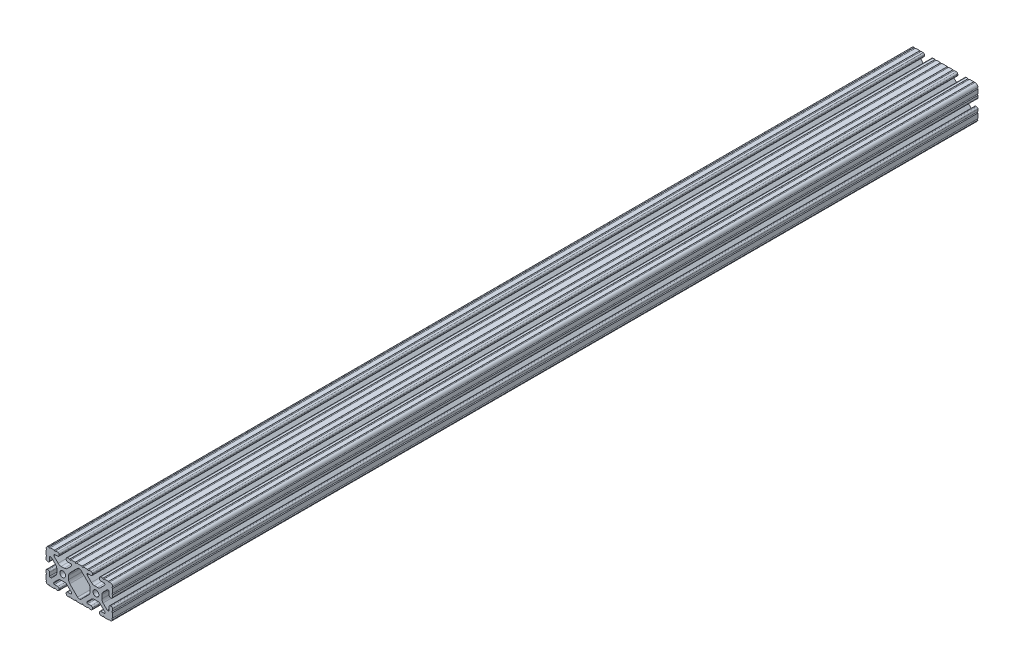
SolidWorks part; units mm, degrees
material "6061 Alloy"
ref_plane "Front Plane" through (0, 0, 0) normal (0, 0, 1) x (1, 0, 0)
ref_plane "Top Plane" through (0, 0, 0) normal (0, 1, 0) x (1, 0, 0)
ref_plane "Right Plane" through (0, 0, 0) normal (1, 0, 0) x (0, 0, -1)
sketch "Sketch1" plane through (0, 0, 0) normal (0, 0, 1) x (1, 0, 0)
  line L0 (-3.1211, -19.05) -> (3.1211, -19.05)
  line L1 (-38.1, 10.287) -> (-38.1, 14.3752)
  line L2 (0, -34.5561) -> (0, 32.8014) construction
  line L3 (-38.1, 0) -> (0, 0) construction
  line L4 (-38.1, 9.5497) -> (-38.1, 10.287)
  line L5 (-19.05, 19.05) -> (-19.05, -20.2827) construction
  line L6 (0, -15.1247) -> (0, -15.1131) construction
  line L7 (9.1761, 12.9058) -> (13.8525, 8.2294)
  line L8 (8.9158, 14.097) -> (8.9158, 13.5344)
  line L9 (13.4112, 14.986) -> (9.8048, 14.986)
  line L10 (14.986, 17.4968) -> (14.986, 16.5608)
  line L11 (10.9975, 19.05) -> (13.4328, 19.05)
  line L12 (8.6331, 19.05) -> (9.4735, 19.05)
  line L13 (4.6451, 19.05) -> (8.6331, 19.05)
  line L14 (31.792, 10.0266) -> (27.1976, 5.4321)
  line L15 (33.147, 10.287) -> (32.4207, 10.287)
  line L16 (29.2071, 19.05) -> (33.2963, 19.05)
  line L17 (28.4698, 19.05) -> (29.2071, 19.05)
  line L18 (-38.1, 5.6388) -> (-38.1, 8.0257)
  line L19 (24.5589, 19.05) -> (26.9458, 19.05)
  line L20 (23.114, 16.5608) -> (23.114, 17.4806)
  line L21 (28.2952, 14.986) -> (24.6888, 14.986)
  line L22 (29.1842, 13.5344) -> (29.1842, 14.097)
  line L23 (-34.036, 9.398) -> (-34.036, 5.6388)
  line L24 (-35.6108, 4.064) -> (-36.5252, 4.064)
  line L25 (24.2475, 8.2294) -> (28.9239, 12.9058)
  line L26 (25.8064, -2.0735) -> (25.8064, 2.0735)
  line L27 (35.6108, 4.064) -> (36.5252, 4.064)
  line L28 (34.036, 9.398) -> (34.036, 5.6388)
  line L29 (38.1, 5.6388) -> (38.1, 8.0257)
  line L30 (38.1, 9.5497) -> (38.1, 10.287)
  line L31 (38.1, 10.287) -> (38.1, 14.3752)
  line L32 (17.2111, 6.8382) -> (20.8889, 6.8382)
  line L33 (2.077, 14.2576) -> (10.9024, 5.4321)
  line L34 (-31.792, -10.0266) -> (-27.1976, -5.4321)
  line L35 (-33.147, -10.287) -> (-32.4207, -10.287)
  line L36 (-29.2071, -19.05) -> (-34.0473, -19.05)
  line L37 (-28.4698, -19.05) -> (-29.2071, -19.05)
  line L38 (-24.6888, -19.05) -> (-26.9458, -19.05)
  line L39 (12.2936, -2.0735) -> (12.2936, 2.0735)
  line L40 (-23.114, -16.5608) -> (-23.114, -17.4752)
  line L41 (-28.448, -14.986) -> (-24.6888, -14.986)
  line L42 (-29.337, -13.6872) -> (-29.337, -14.097)
  line L43 (2.077, -14.2576) -> (10.9024, -5.4321)
  line L44 (-3.1211, 19.05) -> (3.1211, 19.05)
  line L45 (8.763, -14.097) -> (8.763, -13.6872)
  line L46 (-24.2475, -8.2294) -> (-29.0766, -13.0586)
  line L47 (-35.6108, -4.064) -> (-36.5252, -4.064)
  line L48 (-34.036, -9.398) -> (-34.036, -5.6388)
  line L49 (-38.1, -5.6388) -> (-38.1, -8.0257)
  line L50 (-38.1, -9.5497) -> (-38.1, -10.287)
  line L51 (-38.1, -10.287) -> (-38.1, -15.036)
  line L52 (17.2111, -6.8382) -> (20.8889, -6.8382)
  line L53 (38.1, -10.287) -> (38.1, -15.036)
  line L54 (38.1, -9.5497) -> (38.1, -10.287)
  line L55 (38.1, -5.6388) -> (38.1, -8.0257)
  line L56 (34.036, -9.398) -> (34.036, -5.6388)
  line L57 (35.6108, -4.064) -> (36.5252, -4.064)
  line L58 (24.2475, -8.2294) -> (29.0766, -13.0586)
  line L59 (29.337, -13.6872) -> (29.337, -14.097)
  line L60 (-17.2111, -6.8382) -> (-20.8889, -6.8382)
  line L61 (-9.0234, -13.0586) -> (-13.8525, -8.2294)
  line L62 (-8.763, -14.097) -> (-8.763, -13.6872)
  line L63 (-13.4112, -14.986) -> (-9.652, -14.986)
  line L64 (-14.986, -17.4752) -> (-14.986, -16.5608)
  line L65 (-10.9975, -19.05) -> (-13.4112, -19.05)
  line L66 (28.448, -14.986) -> (24.6888, -14.986)
  line L67 (23.114, -16.5608) -> (23.114, -17.4752)
  line L68 (24.6888, -19.05) -> (26.9458, -19.05)
  line L69 (28.4698, -19.05) -> (29.2071, -19.05)
  line L70 (29.2071, -19.05) -> (34.0473, -19.05)
  line L71 (-8.6331, -19.05) -> (-9.4735, -19.05)
  line L72 (33.147, -10.287) -> (32.4207, -10.287)
  line L73 (31.792, -10.0266) -> (27.1976, -5.4321)
  line L74 (-4.6451, -19.05) -> (-8.6331, -19.05)
  line L75 (9.0234, -13.0586) -> (13.8525, -8.2294)
  line L76 (13.4112, -14.986) -> (9.652, -14.986)
  line L77 (-2.077, -14.2576) -> (-10.9024, -5.4321)
  line L78 (14.986, -17.4752) -> (14.986, -16.5608)
  line L79 (10.9975, -19.05) -> (13.4112, -19.05)
  line L80 (4.6451, -19.05) -> (8.6331, -19.05)
  line L81 (8.6331, -19.05) -> (9.4735, -19.05)
  line L83 (-12.2936, -2.0735) -> (-12.2936, 2.0735)
  line L84 (-25.8064, -2.0735) -> (-25.8064, 2.0735)
  line L85 (-2.077, 14.2576) -> (-10.9024, 5.4321)
  line L87 (-4.6451, 19.05) -> (-8.6331, 19.05)
  line L88 (-8.6331, 19.05) -> (-9.4735, 19.05)
  line L89 (-10.9975, 19.05) -> (-13.4328, 19.05)
  line L90 (-14.986, 17.4968) -> (-14.986, 16.5608)
  line L91 (-13.4112, 14.986) -> (-9.8048, 14.986)
  line L92 (-8.9158, 14.097) -> (-8.9158, 13.5344)
  line L93 (-9.1761, 12.9058) -> (-13.8525, 8.2294)
  line L94 (-17.2111, 6.8382) -> (-20.8889, 6.8382)
  line L95 (-24.2475, 8.2294) -> (-28.9239, 12.9058)
  line L96 (-29.1842, 13.5344) -> (-29.1842, 14.097)
  line L97 (-28.2952, 14.986) -> (-24.6888, 14.986)
  line L98 (-23.114, 16.5608) -> (-23.114, 17.4806)
  line L99 (-24.5589, 19.05) -> (-26.9458, 19.05)
  line L100 (-28.4698, 19.05) -> (-29.2071, 19.05)
  line L101 (-29.2071, 19.05) -> (-33.2963, 19.05)
  line L109 (-33.147, 10.287) -> (-32.4207, 10.287)
  line L165 (-31.792, 10.0266) -> (-27.1976, 5.4321)
  arc A0 (-38.1376, 15.8983) -> (-38.1, 14.3752) centre (-38.1, 15.1372) cw
  arc A1 (-38.1, 9.5497) -> (-38.1, 8.0257) centre (-38.1, 8.7877) cw
  arc A2 (9.1761, 12.9058) -> (8.9158, 13.5344) centre (9.8048, 13.5344) cw
  arc A3 (8.9158, 14.097) -> (9.8048, 14.986) centre (9.8048, 14.097) cw
  arc A4 (-36.5252, 4.064) -> (-38.1, 5.6388) centre (-36.5252, 5.6388) cw
  arc A5 (14.986, 16.5608) -> (13.4112, 14.986) centre (13.4112, 16.5608) cw
  arc A6 (13.4328, 19.05) -> (14.986, 17.4968) centre (13.4328, 17.4968) cw
  arc A7 (10.9975, 19.05) -> (9.4735, 19.05) centre (10.2355, 19.05) cw
  arc A8 (4.6451, 19.05) -> (3.1211, 19.05) centre (3.8831, 19.05) cw
  arc A9 (0, 15.1131) -> (2.077, 14.2576) centre (0.0116, 12.1921) cw
  arc A10 (25.8064, 2.0735) -> (27.1976, 5.4321) centre (30.5562, 2.0735) cw
  arc A11 (31.792, 10.0266) -> (32.4207, 10.287) centre (32.4207, 9.398) cw
  arc A12 (33.147, 10.287) -> (34.036, 9.398) centre (33.147, 9.398) cw
  arc A13 (34.8195, 19.0968) -> (38.1376, 15.8983) centre (34.903, 15.8631) cw
  arc A14 (34.8195, 19.0968) -> (33.2963, 19.05) centre (34.0579, 19.0734) cw
  arc A15 (28.4698, 19.05) -> (26.9458, 19.05) centre (27.7078, 19.05) cw
  arc A16 (23.114, 17.4806) -> (24.5589, 19.05) centre (24.6888, 17.4806) cw
  arc A17 (24.6888, 14.986) -> (23.114, 16.5608) centre (24.6888, 16.5608) cw
  arc A18 (28.2952, 14.986) -> (29.1842, 14.097) centre (28.2952, 14.097) cw
  arc A19 (29.1842, 13.5344) -> (28.9239, 12.9058) centre (28.2952, 13.5344) cw
  arc A20 (-35.5713, -19.05) -> (-38.1, -16.56) centre (-34.9455, -15.8855) cw
  arc A21 (34.036, 5.6388) -> (35.6108, 4.064) centre (35.6108, 5.6388) ccw
  arc A22 (36.5252, 4.064) -> (38.1, 5.6388) centre (36.5252, 5.6388) ccw
  arc A23 (38.1, 9.5497) -> (38.1, 8.0257) centre (38.1, 8.7877) ccw
  arc A24 (24.2475, 8.2294) -> (20.8889, 6.8382) centre (20.8889, 11.588) cw
  arc A25 (17.2111, 6.8382) -> (13.8525, 8.2294) centre (17.2111, 11.588) cw
  arc A26 (10.9024, 5.4321) -> (12.2936, 2.0735) centre (7.5438, 2.0735) cw
  arc A27 (0, -15.1131) -> (2.077, -14.2576) centre (0.0116, -12.1921) ccw
  arc A28 (-34.036, 5.6388) -> (-35.6108, 4.064) centre (-35.6108, 5.6388) cw
  arc A29 (-25.8064, -2.0735) -> (-27.1976, -5.4321) centre (-30.5562, -2.0735) cw
  arc A30 (-31.792, -10.0266) -> (-32.4207, -10.287) centre (-32.4207, -9.398) cw
  arc A31 (-33.147, -10.287) -> (-34.036, -9.398) centre (-33.147, -9.398) cw
  arc A33 (-35.5713, -19.05) -> (-34.0473, -19.05) centre (-34.8093, -19.05) cw
  arc A34 (-28.4698, -19.05) -> (-26.9458, -19.05) centre (-27.7078, -19.05) cw
  arc A35 (10.9024, -5.4321) -> (12.2936, -2.0735) centre (7.5438, -2.0735) ccw
  circle A36 centre (19.05, 0) radius 3.3274
  arc A37 (-23.114, -17.4752) -> (-24.6888, -19.05) centre (-24.6888, -17.4752) cw
  arc A38 (-24.6888, -14.986) -> (-23.114, -16.5608) centre (-24.6888, -16.5608) cw
  arc A39 (-28.448, -14.986) -> (-29.337, -14.097) centre (-28.448, -14.097) cw
  arc A40 (-29.337, -13.6872) -> (-29.0766, -13.0586) centre (-28.448, -13.6872) cw
  arc A41 (-24.2475, -8.2294) -> (-20.8889, -6.8382) centre (-20.8889, -11.588) cw
  arc A42 (-34.036, -5.6388) -> (-35.6108, -4.064) centre (-35.6108, -5.6388) ccw
  arc A43 (-36.5252, -4.064) -> (-38.1, -5.6388) centre (-36.5252, -5.6388) ccw
  arc A44 (-38.1, -9.5497) -> (-38.1, -8.0257) centre (-38.1, -8.7877) ccw
  arc A45 (-38.1, -16.56) -> (-38.1, -15.036) centre (-38.1, -15.798) ccw
  arc A46 (38.1, -16.56) -> (38.1, -15.036) centre (38.1, -15.798) cw
  arc A47 (38.1, -9.5497) -> (38.1, -8.0257) centre (38.1, -8.7877) cw
  arc A48 (36.5252, -4.064) -> (38.1, -5.6388) centre (36.5252, -5.6388) cw
  arc A49 (34.036, -5.6388) -> (35.6108, -4.064) centre (35.6108, -5.6388) cw
  arc A50 (24.2475, -8.2294) -> (20.8889, -6.8382) centre (20.8889, -11.588) ccw
  arc A51 (29.337, -13.6872) -> (29.0766, -13.0586) centre (28.448, -13.6872) ccw
  arc A52 (28.448, -14.986) -> (29.337, -14.097) centre (28.448, -14.097) ccw
  arc A53 (24.6888, -14.986) -> (23.114, -16.5608) centre (24.6888, -16.5608) ccw
  arc A54 (-17.2111, -6.8382) -> (-13.8525, -8.2294) centre (-17.2111, -11.588) cw
  arc A55 (-9.0234, -13.0586) -> (-8.763, -13.6872) centre (-9.652, -13.6872) cw
  arc A56 (-8.763, -14.097) -> (-9.652, -14.986) centre (-9.652, -14.097) cw
  arc A57 (-14.986, -16.5608) -> (-13.4112, -14.986) centre (-13.4112, -16.5608) cw
  arc A58 (-13.4112, -19.05) -> (-14.986, -17.4752) centre (-13.4112, -17.4752) cw
  arc A59 (-10.9975, -19.05) -> (-9.4735, -19.05) centre (-10.2355, -19.05) cw
  arc A60 (-4.6451, -19.05) -> (-3.1211, -19.05) centre (-3.8831, -19.05) cw
  arc A61 (23.114, -17.4752) -> (24.6888, -19.05) centre (24.6888, -17.4752) ccw
  arc A62 (28.4698, -19.05) -> (26.9458, -19.05) centre (27.7078, -19.05) ccw
  arc A63 (35.5713, -19.05) -> (34.0473, -19.05) centre (34.8093, -19.05) ccw
  arc A64 (35.5713, -19.05) -> (38.1, -16.56) centre (34.9379, -15.8778) ccw
  arc A65 (33.147, -10.287) -> (34.036, -9.398) centre (33.147, -9.398) ccw
  arc A66 (31.792, -10.0266) -> (32.4207, -10.287) centre (32.4207, -9.398) ccw
  arc A67 (-10.9024, -5.4321) -> (-12.2936, -2.0735) centre (-7.5438, -2.0735) cw
  arc A68 (0, -15.1131) -> (-2.077, -14.2576) centre (-0.0116, -12.1921) cw
  arc A69 (0, 15.1131) -> (-2.077, 14.2576) centre (-0.0116, 12.1921) ccw
  arc A70 (-10.9024, 5.4321) -> (-12.2936, 2.0735) centre (-7.5438, 2.0735) ccw
  arc A71 (25.8064, -2.0735) -> (27.1976, -5.4321) centre (30.5562, -2.0735) ccw
  arc A72 (9.0234, -13.0586) -> (8.763, -13.6872) centre (9.652, -13.6872) ccw
  arc A73 (8.763, -14.097) -> (9.652, -14.986) centre (9.652, -14.097) ccw
  arc A74 (17.2111, -6.8382) -> (13.8525, -8.2294) centre (17.2111, -11.588) ccw
  arc A75 (13.4112, -19.05) -> (14.986, -17.4752) centre (13.4112, -17.4752) ccw
  arc A76 (14.986, -16.5608) -> (13.4112, -14.986) centre (13.4112, -16.5608) ccw
  arc A77 (-4.6451, 19.05) -> (-3.1211, 19.05) centre (-3.8831, 19.05) ccw
  arc A78 (-10.9975, 19.05) -> (-9.4735, 19.05) centre (-10.2355, 19.05) ccw
  arc A79 (-13.4328, 19.05) -> (-14.986, 17.4968) centre (-13.4328, 17.4968) ccw
  arc A80 (-14.986, 16.5608) -> (-13.4112, 14.986) centre (-13.4112, 16.5608) ccw
  arc A81 (-8.9158, 14.097) -> (-9.8048, 14.986) centre (-9.8048, 14.097) ccw
  arc A82 (-9.1761, 12.9058) -> (-8.9158, 13.5344) centre (-9.8048, 13.5344) ccw
  arc A83 (-17.2111, 6.8382) -> (-13.8525, 8.2294) centre (-17.2111, 11.588) ccw
  arc A84 (-24.2475, 8.2294) -> (-20.8889, 6.8382) centre (-20.8889, 11.588) ccw
  arc A85 (-29.1842, 13.5344) -> (-28.9239, 12.9058) centre (-28.2952, 13.5344) ccw
  arc A86 (-28.2952, 14.986) -> (-29.1842, 14.097) centre (-28.2952, 14.097) ccw
  arc A87 (-24.6888, 14.986) -> (-23.114, 16.5608) centre (-24.6888, 16.5608) ccw
  arc A88 (-23.114, 17.4806) -> (-24.5589, 19.05) centre (-24.6888, 17.4806) ccw
  arc A89 (-28.4698, 19.05) -> (-26.9458, 19.05) centre (-27.7078, 19.05) ccw
  arc A90 (-34.8195, 19.0968) -> (-33.2963, 19.05) centre (-34.0579, 19.0734) ccw
  arc A91 (-34.8195, 19.0968) -> (-38.1376, 15.8983) centre (-34.903, 15.8631) ccw
  arc A92 (4.6451, -19.05) -> (3.1211, -19.05) centre (3.8831, -19.05) ccw
  arc A93 (10.9975, -19.05) -> (9.4735, -19.05) centre (10.2355, -19.05) ccw
  arc A94 (38.1376, 15.8983) -> (38.1, 14.3752) centre (38.1, 15.1372) ccw
  arc A96 (-33.147, 10.287) -> (-34.036, 9.398) centre (-33.147, 9.398) ccw
  arc A97 (-31.792, 10.0266) -> (-32.4207, 10.287) centre (-32.4207, 9.398) ccw
  arc A98 (-25.8064, 2.0735) -> (-27.1976, 5.4321) centre (-30.5562, 2.0735) ccw
  circle A101 centre (-19.05, 0) radius 3.3274
  point P34 (0, 19.05)
  point P79 (25.6765, 0)
  point P274 (0, -19.05)
  point P282 (-25.6765, 0)
  point P283 (-12.2936, 0)
  dimension "D1" = 38.1
  dimension "D4" = 6.6548
  dimension "D10" = 4.064
  dimension "D2" = 76.2
  dimension "D3" = 38.1
  dimension "D5" = 8.128
  dimension "D6" = 20.574
  dimension "D7" = 12.2936
  dimension "D8" = 4.064
  dimension "D9" = 4.064
extrude "Extrude1" add sketch "Sketch1" against normal blind 990.6
